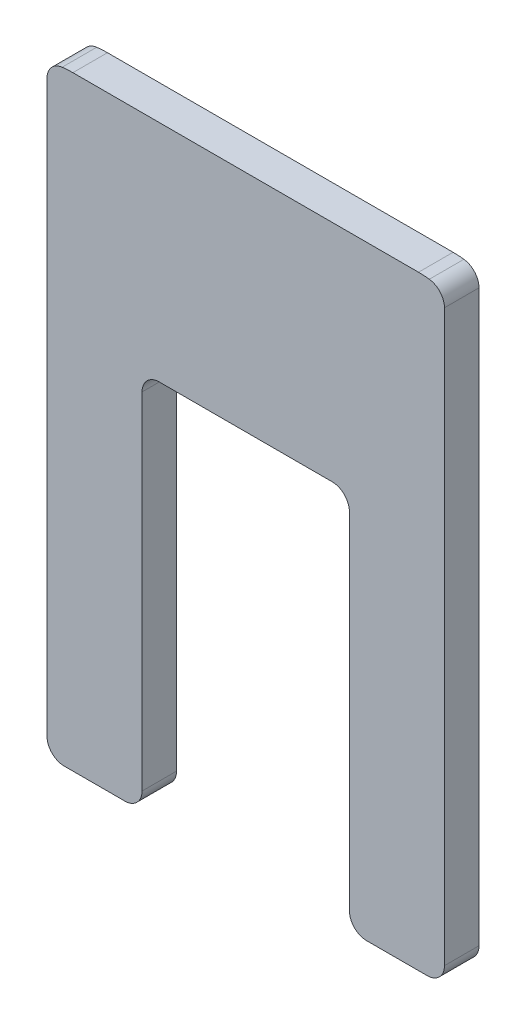
SolidWorks part; units mm, degrees
ref_plane "Front Plane" through (0, 0, 0) normal (0, 0, 1) x (1, 0, 0)
ref_plane "Top Plane" through (0, 0, 0) normal (0, 1, 0) x (1, 0, 0)
ref_plane "Right Plane" through (0, 0, 0) normal (1, 0, 0) x (0, 0, -1)
sketch "Sketch1" plane through (0, 0, 0) normal (0, 0, 1) x (1, 0, 0)
  line L1 (0, 0) -> (23, 0)
  line L2 (0, 0) -> (0, 34.7697)
  line L3 (1.5, 35) -> (21.5, 35)
  line L4 (23, 0) -> (23, 34.7697)
  arc A0 (0, 34.7697) -> (1.5, 35) centre (1.5, 30) cw
  arc A1 (23, 34.7697) -> (21.5, 35) centre (21.5, 30) ccw
  point P1 (11.5, 35)
  point P2 (11.5, 0)
  dimension "D4" = 5
  dimension "D2" = 35
  dimension "D5" = 5
  dimension "D1" = 23
  dimension "D3" = 20
extrude "Boss-Extrude1" add sketch "Sketch1" along normal blind 2
fillet "Fillet2" radius 1 4 edges at (23, 0, 1) (0, 0, 1) (0, 34.7697, 1) (23, 34.7697, 1)
sketch "Sketch2" plane through (0, 0, 2) normal (0, 0, 1) x (1, 0, 0)
  line L0 (1, 0) -> (22, 0) construction
  line L1 (5.5, 0) -> (17.5, 0)
  line L2 (5.5, 0) -> (5.5, 22)
  line L3 (5.5, 22) -> (17.5, 22)
  line L4 (17.5, 0) -> (17.5, 22)
  point P6 (11.5, 0)
  point P7 (11.5, 0)
  point P8 (0, 0)
  dimension "D1" = 12
  dimension "D2" = 22
extrude "Cut-Extrude1" cut sketch "Sketch2" against normal blind 10 contours L3 L4 L1 L2
fillet "Fillet3" radius 1 4 edges at (5.5, 0, 1) (17.5, 0, 1) (17.5, 22, 1) (5.5, 22, 1)
